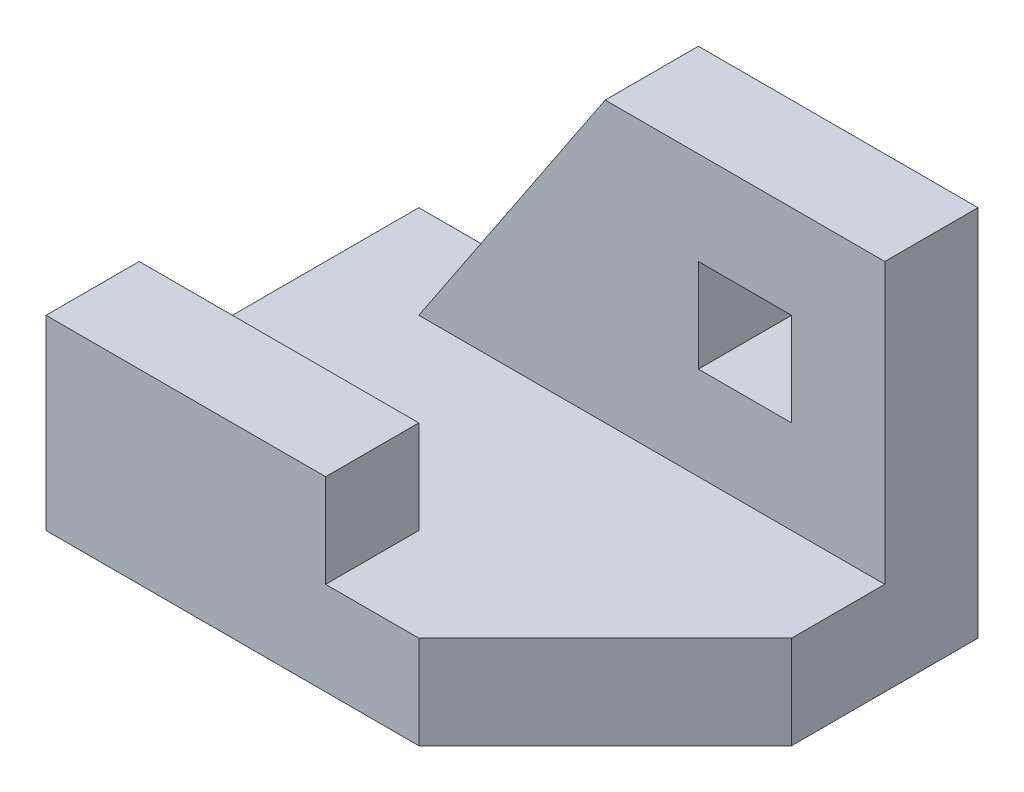
SolidWorks part; units mm, degrees
ref_plane "Front Plane" through (0, 0, 0) normal (0, 0, 1) x (1, 0, 0)
ref_plane "Top Plane" through (0, 0, 0) normal (0, 1, 0) x (1, 0, 0)
ref_plane "Right Plane" through (0, 0, 0) normal (1, 0, 0) x (0, 0, -1)
sketch "Sketch1" plane through (0, 0, 0) normal (0, 1, 0) x (1, 0, 0)
  line L1 (-30, 20) -> (30, 20)
  line L2 (-30, 20) -> (-30, -20)
  line L3 (-30, -20) -> (30, -20)
  line L4 (30, 20) -> (30, -20)
  line L5 (-30, 20) -> (30, -20) construction
  line L6 (-30, -20) -> (30, 20) construction
  point P0 (0, 0)
  dimension "D1" = 60
  dimension "D2" = 40
extrude "Boss-Extrude1" add sketch "Sketch1" along normal blind 10
chamfer "Chamfer1" distance 20 angle 45 1 edges at (30, 5, 20)
sketch "Sketch2" plane through (0, 10, 0) normal (0, 1, 0) x (1, 0, 0)
  line L1 (-30, -20) -> (0, -20)
  line L2 (-30, -20) -> (-30, -10)
  line L3 (-30, -10) -> (0, -10)
  line L4 (0, -20) -> (0, -10)
  dimension "D1" = 30
  dimension "D2" = 10
extrude "Boss-Extrude2" add sketch "Sketch2" along normal blind 10
sketch "Sketch3" plane through (0, 0, -20) normal (0, 0, -1) x (-1, 0, 0)
  line L0 (-30, 10) -> (-30, 40)
  line L1 (-30, 40) -> (0, 40)
  line L2 (0, 40) -> (20, 10)
  line L3 (-30, 10) -> (30, 10) construction
  line L4 (20, 10) -> (-30, 10)
  line L6 (-20, 30) -> (-10, 30)
  line L7 (-20, 30) -> (-20, 20)
  line L8 (-20, 20) -> (-10, 20)
  line L9 (-10, 30) -> (-10, 20)
  dimension "D1" = 30
  dimension "D2" = 30
  dimension "D3" = 50
  dimension "D4" = 10
  dimension "D5" = 10
  dimension "D6" = 10
extrude "Boss-Extrude3" add sketch "Sketch3" against normal blind 10
